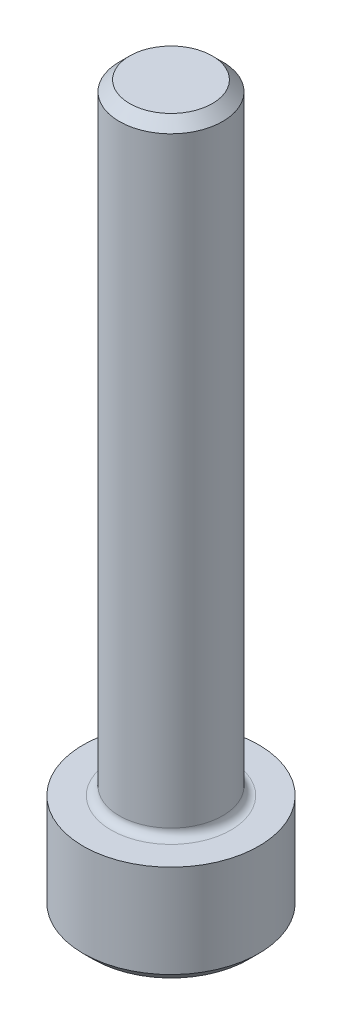
SolidWorks part; units mm, degrees
ref_plane "Front Plane" through (0, 0, 0) normal (0, 0, 1) x (1, 0, 0)
ref_plane "Top Plane" through (0, 0, 0) normal (0, 1, 0) x (1, 0, 0)
ref_plane "Right Plane" through (0, 0, 0) normal (1, 0, 0) x (0, 0, -1)
sketch "Sketch2" plane through (0, 0, 0) normal (0, 1, 0) x (1, 0, 0)
  circle A0 centre (0, 0) radius 2.5
extrude "Boss-Extrude1" add sketch "Sketch2" along normal blind 30
sketch "Sketch3" plane through (0, 0, 0) normal (0, 1, 0) x (1, 0, 0)
  circle A0 centre (0, 0) radius 4.25
extrude "Boss-Extrude2" add sketch "Sketch3" against normal blind 5
fillet "Fillet1" radius 0.4 1 edges at (0, 0, 2.5)
chamfer "Chamfer1" distance 0.5 angle 45 2 edges at (0, 30, 2.5) (0, -5, 4.25)
sketch "Sketch4" plane through (0, -5, 0) normal (0, -1, 0) x (1, 0, 0)
  line L1 (0, 2.3094) -> (-2, 1.1547)
  line L2 (-2, 1.1547) -> (-2, -1.1547)
  line L3 (-2, -1.1547) -> (0, -2.3094)
  line L4 (0, -2.3094) -> (2, -1.1547)
  line L5 (2, -1.1547) -> (2, 1.1547)
  line L6 (2, 1.1547) -> (0, 2.3094)
  circle A0 centre (0, 0) radius 2 construction
extrude "Cut-Extrude1" cut sketch "Sketch4" against normal blind 2.5
